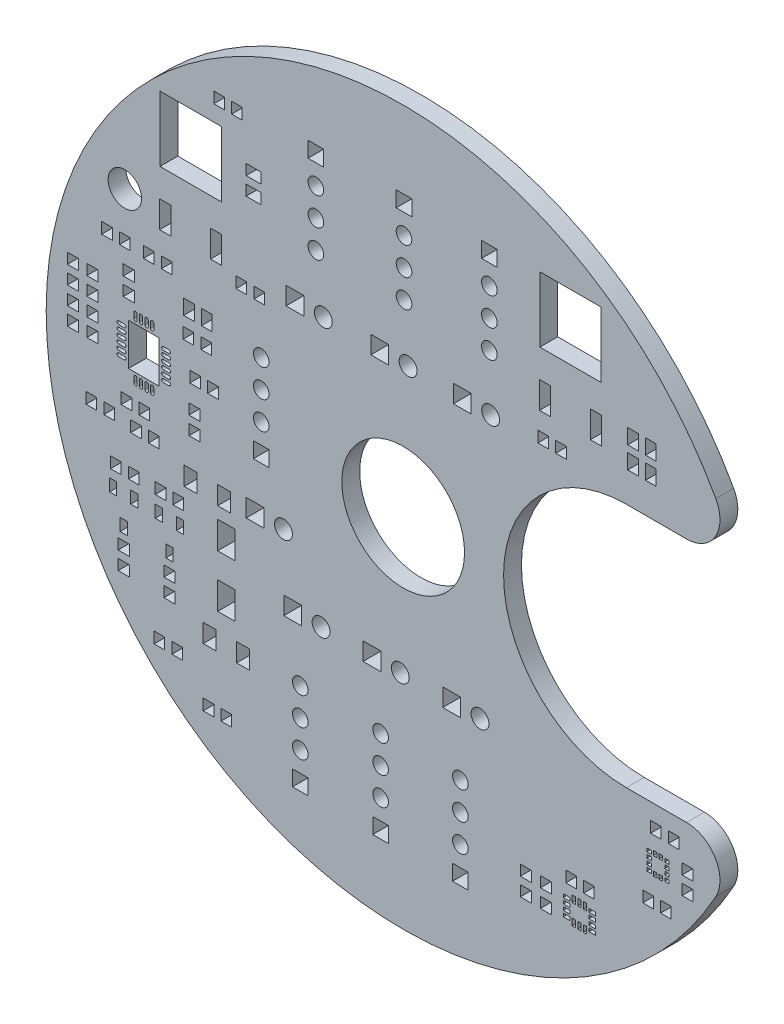
SolidWorks part; units mm, degrees
ref_plane "Plan de face" through (0, 0, 0) normal (0, 0, 1) x (1, 0, 0)
ref_plane "Plan de dessus" through (0, 0, 0) normal (0, 1, 0) x (1, 0, 0)
ref_plane "Plan de droite" through (0, 0, 0) normal (1, 0, 0) x (0, 0, -1)
sketch "Model" plane through (0, 0, 0) normal (0, 0, 1) x (1, 0, 0)
  line L0 (23.85, -16.25) -> (23.85, -16.55)
  line L1 (23.85, -16.55) -> (23.45, -16.55)
  line L2 (23.45, -16.55) -> (23.45, -16.25)
  line L3 (23.45, -16.25) -> (23.85, -16.25)
  line L4 (23.85, -15.75) -> (23.85, -16.05)
  line L5 (23.85, -16.05) -> (23.45, -16.05)
  line L6 (23.45, -16.05) -> (23.45, -15.75)
  line L7 (23.45, -15.75) -> (23.85, -15.75)
  line L8 (23.85, -15.25) -> (23.85, -15.55)
  line L9 (23.85, -15.55) -> (23.45, -15.55)
  line L10 (23.45, -15.55) -> (23.45, -15.25)
  line L11 (23.45, -15.25) -> (23.85, -15.25)
  line L12 (23.85, -14.75) -> (23.85, -15.05)
  line L13 (23.85, -15.05) -> (23.45, -15.05)
  line L14 (23.45, -15.05) -> (23.45, -14.75)
  line L15 (23.45, -14.75) -> (23.85, -14.75)
  line L16 (22.95, -14.65) -> (23.25, -14.65)
  line L17 (23.25, -14.65) -> (23.25, -15.05)
  line L18 (23.25, -15.05) -> (22.95, -15.05)
  line L19 (22.95, -15.05) -> (22.95, -14.65)
  line L20 (22.45, -14.65) -> (22.75, -14.65)
  line L21 (22.75, -14.65) -> (22.75, -15.05)
  line L22 (22.75, -15.05) -> (22.45, -15.05)
  line L23 (22.45, -15.05) -> (22.45, -14.65)
  line L24 (22.25, -14.75) -> (22.25, -15.05)
  line L25 (22.25, -15.05) -> (21.85, -15.05)
  line L26 (21.85, -15.05) -> (21.85, -14.75)
  line L27 (21.85, -14.75) -> (22.25, -14.75)
  line L28 (22.25, -15.25) -> (22.25, -15.55)
  line L29 (22.25, -15.55) -> (21.85, -15.55)
  line L30 (21.85, -15.55) -> (21.85, -15.25)
  line L31 (21.85, -15.25) -> (22.25, -15.25)
  line L32 (22.25, -15.75) -> (22.25, -16.05)
  line L33 (22.25, -16.05) -> (21.85, -16.05)
  line L34 (21.85, -16.05) -> (21.85, -15.75)
  line L35 (21.85, -15.75) -> (22.25, -15.75)
  line L36 (22.25, -16.25) -> (22.25, -16.55)
  line L37 (22.25, -16.55) -> (21.85, -16.55)
  line L38 (21.85, -16.55) -> (21.85, -16.25)
  line L39 (21.85, -16.25) -> (22.25, -16.25)
  line L40 (22.45, -16.25) -> (22.75, -16.25)
  line L41 (22.75, -16.25) -> (22.75, -16.65)
  line L42 (22.75, -16.65) -> (22.45, -16.65)
  line L43 (22.45, -16.65) -> (22.45, -16.25)
  line L44 (22.95, -16.25) -> (23.25, -16.25)
  line L45 (23.25, -16.25) -> (23.25, -16.65)
  line L46 (23.25, -16.65) -> (22.95, -16.65)
  line L47 (22.95, -16.65) -> (22.95, -16.25)
  line L48 (17.25, -23.55) -> (17.25, -23.85)
  line L49 (17.25, -23.85) -> (16.65, -23.85)
  line L50 (16.65, -23.85) -> (16.65, -23.55)
  line L51 (16.65, -23.55) -> (17.25, -23.55)
  line L52 (17.25, -23.05) -> (17.25, -23.35)
  line L53 (17.25, -23.35) -> (16.65, -23.35)
  line L54 (16.65, -23.35) -> (16.65, -23.05)
  line L55 (16.65, -23.05) -> (17.25, -23.05)
  line L56 (17.25, -22.55) -> (17.25, -22.85)
  line L57 (17.25, -22.85) -> (16.65, -22.85)
  line L58 (16.65, -22.85) -> (16.65, -22.55)
  line L59 (16.65, -22.55) -> (17.25, -22.55)
  line L60 (17.25, -22.05) -> (17.25, -22.35)
  line L61 (17.25, -22.35) -> (16.65, -22.35)
  line L62 (16.65, -22.35) -> (16.65, -22.05)
  line L63 (16.65, -22.05) -> (17.25, -22.05)
  line L64 (16.15, -21.75) -> (16.45, -21.75)
  line L65 (16.45, -21.75) -> (16.45, -22.35)
  line L66 (16.45, -22.35) -> (16.15, -22.35)
  line L67 (16.15, -22.35) -> (16.15, -21.75)
  line L68 (15.65, -21.75) -> (15.95, -21.75)
  line L69 (15.95, -21.75) -> (15.95, -22.35)
  line L70 (15.95, -22.35) -> (15.65, -22.35)
  line L71 (15.65, -22.35) -> (15.65, -21.75)
  line L72 (15.15, -21.75) -> (15.45, -21.75)
  line L73 (15.45, -21.75) -> (15.45, -22.35)
  line L74 (15.45, -22.35) -> (15.15, -22.35)
  line L75 (15.15, -22.35) -> (15.15, -21.75)
  line L76 (14.95, -22.05) -> (14.95, -22.35)
  line L77 (14.95, -22.35) -> (14.35, -22.35)
  line L78 (14.35, -22.35) -> (14.35, -22.05)
  line L79 (14.35, -22.05) -> (14.95, -22.05)
  line L80 (14.95, -22.55) -> (14.95, -22.85)
  line L81 (14.95, -22.85) -> (14.35, -22.85)
  line L82 (14.35, -22.85) -> (14.35, -22.55)
  line L83 (14.35, -22.55) -> (14.95, -22.55)
  line L84 (14.95, -23.05) -> (14.95, -23.35)
  line L85 (14.95, -23.35) -> (14.35, -23.35)
  line L86 (14.35, -23.35) -> (14.35, -23.05)
  line L87 (14.35, -23.05) -> (14.95, -23.05)
  line L88 (14.95, -23.55) -> (14.95, -23.85)
  line L89 (14.95, -23.85) -> (14.35, -23.85)
  line L90 (14.35, -23.85) -> (14.35, -23.55)
  line L91 (14.35, -23.55) -> (14.95, -23.55)
  line L92 (15.15, -23.55) -> (15.45, -23.55)
  line L93 (15.45, -23.55) -> (15.45, -24.15)
  line L94 (15.45, -24.15) -> (15.15, -24.15)
  line L95 (15.15, -24.15) -> (15.15, -23.55)
  line L96 (15.65, -23.55) -> (15.95, -23.55)
  line L97 (15.95, -23.55) -> (15.95, -24.15)
  line L98 (15.95, -24.15) -> (15.65, -24.15)
  line L99 (15.65, -24.15) -> (15.65, -23.55)
  line L100 (16.15, -23.55) -> (16.45, -23.55)
  line L101 (16.45, -23.55) -> (16.45, -24.15)
  line L102 (16.45, -24.15) -> (16.15, -24.15)
  line L103 (16.15, -24.15) -> (16.15, -23.55)
  line L104 (-18.075, 7.175) -> (-17.125, 7.175)
  line L105 (-17.125, 7.175) -> (-17.125, 5.825)
  line L106 (-17.125, 5.825) -> (-18.075, 5.825)
  line L107 (-18.075, 5.825) -> (-18.075, 7.175)
  line L108 (-19.675, 7.175) -> (-18.725, 7.175)
  line L109 (-18.725, 7.175) -> (-18.725, 5.825)
  line L110 (-18.725, 5.825) -> (-19.675, 5.825)
  line L111 (-19.675, 5.825) -> (-19.675, 7.175)
  line L112 (-21.5, 0) -> (-21, 0)
  line L113 (-21, -0.3) -> (-21.5, -0.3)
  line L114 (-21.5, 0.5) -> (-21, 0.5)
  line L115 (-21, 0.2) -> (-21.5, 0.2)
  line L116 (-21.5, 1) -> (-21, 1)
  line L117 (-21, 0.7) -> (-21.5, 0.7)
  line L118 (-21.5, 1.5) -> (-21, 1.5)
  line L119 (-21, 1.2) -> (-21.5, 1.2)
  line L120 (-21.5, 2) -> (-21, 2)
  line L121 (-21, 1.7) -> (-21.5, 1.7)
  line L122 (-21.5, 2.5) -> (-21, 2.5)
  line L123 (-21, 2.2) -> (-21.5, 2.2)
  line L124 (-22.65, 3.35) -> (-22.65, 3.85)
  line L125 (-22.35, 3.85) -> (-22.35, 3.35)
  line L126 (-23.15, 3.35) -> (-23.15, 3.85)
  line L127 (-22.85, 3.85) -> (-22.85, 3.35)
  line L128 (-23.65, 3.35) -> (-23.65, 3.85)
  line L129 (-23.35, 3.85) -> (-23.35, 3.35)
  line L130 (-24.15, 3.35) -> (-24.15, 3.85)
  line L131 (-23.85, 3.85) -> (-23.85, 3.35)
  line L132 (-25.5, 2.5) -> (-25, 2.5)
  line L133 (-25, 2.2) -> (-25.5, 2.2)
  line L134 (-25.5, 2) -> (-25, 2)
  line L135 (-25, 1.7) -> (-25.5, 1.7)
  line L136 (-25.5, 1.5) -> (-25, 1.5)
  line L137 (-25, 1.2) -> (-25.5, 1.2)
  line L138 (-25.5, 1) -> (-25, 1)
  line L139 (-25, 0.7) -> (-25.5, 0.7)
  line L140 (-25.5, 0.5) -> (-25, 0.5)
  line L141 (-25, 0.2) -> (-25.5, 0.2)
  line L142 (-25.5, 0) -> (-25, 0)
  line L143 (-25, -0.3) -> (-25.5, -0.3)
  line L144 (-24.15, -1.65) -> (-24.15, -1.15)
  line L145 (-23.85, -1.15) -> (-23.85, -1.65)
  line L146 (-23.65, -1.65) -> (-23.65, -1.15)
  line L147 (-23.35, -1.15) -> (-23.35, -1.65)
  line L148 (-23.15, -1.65) -> (-23.15, -1.15)
  line L149 (-22.85, -1.15) -> (-22.85, -1.65)
  line L150 (-22.65, -1.65) -> (-22.65, -1.15)
  line L151 (-22.35, -1.15) -> (-22.35, -1.65)
  line L152 (-21.875, 2.975) -> (-21.875, -0.775)
  line L153 (-21.875, -0.775) -> (-24.625, -0.775)
  line L154 (-24.625, -0.775) -> (-24.625, 2.975)
  line L155 (-24.625, 2.975) -> (-21.875, 2.975)
  line L156 (-24.425, -10.1) -> (-23.775, -10.1)
  line L157 (-23.775, -10.1) -> (-23.775, -11.2)
  line L158 (-23.775, -11.2) -> (-24.425, -11.2)
  line L159 (-24.425, -11.2) -> (-24.425, -10.1)
  line L160 (-26.325, -10.1) -> (-25.675, -10.1)
  line L161 (-25.675, -10.1) -> (-25.675, -11.2)
  line L162 (-25.675, -11.2) -> (-26.325, -11.2)
  line L163 (-26.325, -11.2) -> (-26.325, -10.1)
  line L164 (-25.375, -12.7) -> (-24.725, -12.7)
  line L165 (-24.725, -12.7) -> (-24.725, -13.8)
  line L166 (-24.725, -13.8) -> (-25.375, -13.8)
  line L167 (-25.375, -13.8) -> (-25.375, -12.7)
  line L168 (-20.325, -10.1) -> (-19.675, -10.1)
  line L169 (-19.675, -10.1) -> (-19.675, -11.2)
  line L170 (-19.675, -11.2) -> (-20.325, -11.2)
  line L171 (-20.325, -11.2) -> (-20.325, -10.1)
  line L172 (-22.225, -10.1) -> (-21.575, -10.1)
  line L173 (-21.575, -10.1) -> (-21.575, -11.2)
  line L174 (-21.575, -11.2) -> (-22.225, -11.2)
  line L175 (-22.225, -11.2) -> (-22.225, -10.1)
  line L176 (-21.275, -12.7) -> (-20.625, -12.7)
  line L177 (-20.625, -12.7) -> (-20.625, -13.8)
  line L178 (-20.625, -13.8) -> (-21.275, -13.8)
  line L179 (-21.275, -13.8) -> (-21.275, -12.7)
  line L180 (21.725, 15.075) -> (22.675, 15.075)
  line L181 (22.675, 15.075) -> (22.675, 13.725)
  line L182 (22.675, 13.725) -> (21.725, 13.725)
  line L183 (21.725, 13.725) -> (21.725, 15.075)
  line L184 (20.125, 15.075) -> (21.075, 15.075)
  line L185 (21.075, 15.075) -> (21.075, 13.725)
  line L186 (21.075, 13.725) -> (20.125, 13.725)
  line L187 (20.125, 13.725) -> (20.125, 15.075)
  line L188 (-14.075, 19.475) -> (-14.075, 20.425)
  line L189 (-14.075, 20.425) -> (-12.725, 20.425)
  line L190 (-12.725, 20.425) -> (-12.725, 19.475)
  line L191 (-12.725, 19.475) -> (-14.075, 19.475)
  line L192 (-14.075, 17.875) -> (-14.075, 18.825)
  line L193 (-14.075, 18.825) -> (-12.725, 18.825)
  line L194 (-12.725, 18.825) -> (-12.725, 17.875)
  line L195 (-12.725, 17.875) -> (-14.075, 17.875)
  line L196 (21.075, 15.675) -> (20.125, 15.675)
  line L197 (20.125, 15.675) -> (20.125, 17.025)
  line L198 (20.125, 17.025) -> (21.075, 17.025)
  line L199 (21.075, 17.025) -> (21.075, 15.675)
  line L200 (22.675, 15.675) -> (21.725, 15.675)
  line L201 (21.725, 15.675) -> (21.725, 17.025)
  line L202 (21.725, 17.025) -> (22.675, 17.025)
  line L203 (22.675, 17.025) -> (22.675, 15.675)
  line L204 (-20.83, 11.4) -> (-21.83, 11.4)
  line L205 (-21.83, 11.4) -> (-21.83, 13.8)
  line L206 (-21.83, 13.8) -> (-20.83, 13.8)
  line L207 (-20.83, 13.8) -> (-20.83, 11.4)
  line L208 (-16.27, 11.4) -> (-17.27, 11.4)
  line L209 (-17.27, 11.4) -> (-17.27, 13.8)
  line L210 (-17.27, 13.8) -> (-16.27, 13.8)
  line L211 (-16.27, 13.8) -> (-16.27, 11.4)
  line L212 (-16.3, 16.325) -> (-21.8, 16.325)
  line L213 (-21.8, 16.325) -> (-21.8, 22.175)
  line L214 (-21.8, 22.175) -> (-16.3, 22.175)
  line L215 (-16.3, 22.175) -> (-16.3, 16.325)
  line L216 (13.22, 14.4) -> (12.22, 14.4)
  line L217 (12.22, 14.4) -> (12.22, 16.8)
  line L218 (12.22, 16.8) -> (13.22, 16.8)
  line L219 (13.22, 16.8) -> (13.22, 14.4)
  line L220 (17.78, 14.4) -> (16.78, 14.4)
  line L221 (16.78, 14.4) -> (16.78, 16.8)
  line L222 (16.78, 16.8) -> (17.78, 16.8)
  line L223 (17.78, 16.8) -> (17.78, 14.4)
  line L224 (17.75, 19.325) -> (12.25, 19.325)
  line L225 (12.25, 19.325) -> (12.25, 25.175)
  line L226 (12.25, 25.175) -> (17.75, 25.175)
  line L227 (17.75, 25.175) -> (17.75, 19.325)
  line L228 (-16.025, 23.6) -> (-16.975, 23.6)
  line L229 (-16.975, 23.6) -> (-16.975, 24.6)
  line L230 (-16.975, 24.6) -> (-16.025, 24.6)
  line L231 (-16.025, 24.6) -> (-16.025, 23.6)
  line L232 (-14.425, 23.6) -> (-15.375, 23.6)
  line L233 (-15.375, 23.6) -> (-15.375, 24.6)
  line L234 (-15.375, 24.6) -> (-14.425, 24.6)
  line L235 (-14.425, 24.6) -> (-14.425, 23.6)
  line L236 (-20.725, -20) -> (-19.775, -20)
  line L237 (-19.775, -20) -> (-19.775, -21)
  line L238 (-19.775, -21) -> (-20.725, -21)
  line L239 (-20.725, -21) -> (-20.725, -20)
  line L240 (-22.325, -20) -> (-21.375, -20)
  line L241 (-21.375, -20) -> (-21.375, -21)
  line L242 (-21.375, -21) -> (-22.325, -21)
  line L243 (-22.325, -21) -> (-22.325, -20)
  line L244 (-16.975, -24) -> (-17.925, -24)
  line L245 (-17.925, -24) -> (-17.925, -23)
  line L246 (-17.925, -23) -> (-16.975, -23)
  line L247 (-16.975, -23) -> (-16.975, -24)
  line L248 (-15.375, -24) -> (-16.325, -24)
  line L249 (-16.325, -24) -> (-16.325, -23)
  line L250 (-16.325, -23) -> (-15.375, -23)
  line L251 (-15.375, -23) -> (-15.375, -24)
  line L252 (-14.025, 10.25) -> (-14.975, 10.25)
  line L253 (-14.975, 10.25) -> (-14.975, 11.25)
  line L254 (-14.975, 11.25) -> (-14.025, 11.25)
  line L255 (-14.025, 11.25) -> (-14.025, 10.25)
  line L256 (-12.425, 10.25) -> (-13.375, 10.25)
  line L257 (-13.375, 10.25) -> (-13.375, 11.25)
  line L258 (-13.375, 11.25) -> (-12.425, 11.25)
  line L259 (-12.425, 11.25) -> (-12.425, 10.25)
  line L260 (23.775, -12.45) -> (24.725, -12.45)
  line L261 (24.725, -12.45) -> (24.725, -13.45)
  line L262 (24.725, -13.45) -> (23.775, -13.45)
  line L263 (23.775, -13.45) -> (23.775, -12.45)
  line L264 (22.175, -12.45) -> (23.125, -12.45)
  line L265 (23.125, -12.45) -> (23.125, -13.45)
  line L266 (23.125, -13.45) -> (22.175, -13.45)
  line L267 (22.175, -13.45) -> (22.175, -12.45)
  line L268 (23.075, -18.2) -> (24.025, -18.2)
  line L269 (24.025, -18.2) -> (24.025, -19.2)
  line L270 (24.025, -19.2) -> (23.075, -19.2)
  line L271 (23.075, -19.2) -> (23.075, -18.2)
  line L272 (21.475, -18.2) -> (22.425, -18.2)
  line L273 (22.425, -18.2) -> (22.425, -19.2)
  line L274 (22.425, -19.2) -> (21.475, -19.2)
  line L275 (21.475, -19.2) -> (21.475, -18.2)
  line L276 (26, -15.925) -> (26, -16.875)
  line L277 (26, -16.875) -> (25, -16.875)
  line L278 (25, -16.875) -> (25, -15.925)
  line L279 (25, -15.925) -> (26, -15.925)
  line L280 (26, -14.325) -> (26, -15.275)
  line L281 (26, -15.275) -> (25, -15.275)
  line L282 (25, -15.275) -> (25, -14.325)
  line L283 (25, -14.325) -> (26, -14.325)
  line L284 (15.525, -21.1) -> (14.575, -21.1)
  line L285 (14.575, -21.1) -> (14.575, -20.1)
  line L286 (14.575, -20.1) -> (15.525, -20.1)
  line L287 (15.525, -20.1) -> (15.525, -21.1)
  line L288 (17.125, -21.1) -> (16.175, -21.1)
  line L289 (16.175, -21.1) -> (16.175, -20.1)
  line L290 (16.175, -20.1) -> (17.125, -20.1)
  line L291 (17.125, -20.1) -> (17.125, -21.1)
  line L292 (11.5, -23.275) -> (11.5, -24.225)
  line L293 (11.5, -24.225) -> (10.5, -24.225)
  line L294 (10.5, -24.225) -> (10.5, -23.275)
  line L295 (10.5, -23.275) -> (11.5, -23.275)
  line L296 (11.5, -21.675) -> (11.5, -22.625)
  line L297 (11.5, -22.625) -> (10.5, -22.625)
  line L298 (10.5, -22.625) -> (10.5, -21.675)
  line L299 (10.5, -21.675) -> (11.5, -21.675)
  line L300 (13.3, -23.275) -> (13.3, -24.225)
  line L301 (13.3, -24.225) -> (12.3, -24.225)
  line L302 (12.3, -24.225) -> (12.3, -23.275)
  line L303 (12.3, -23.275) -> (13.3, -23.275)
  line L304 (13.3, -21.675) -> (13.3, -22.625)
  line L305 (13.3, -22.625) -> (12.3, -22.625)
  line L306 (12.3, -22.625) -> (12.3, -21.675)
  line L307 (12.3, -21.675) -> (13.3, -21.675)
  line L308 (-18.775, 3.95) -> (-19.725, 3.95)
  line L309 (-19.725, 3.95) -> (-19.725, 4.95)
  line L310 (-19.725, 4.95) -> (-18.775, 4.95)
  line L311 (-18.775, 4.95) -> (-18.775, 3.95)
  line L312 (-17.175, 3.95) -> (-18.125, 3.95)
  line L313 (-18.125, 3.95) -> (-18.125, 4.95)
  line L314 (-18.125, 4.95) -> (-17.175, 4.95)
  line L315 (-17.175, 4.95) -> (-17.175, 3.95)
  line L316 (-23.675, -2.9) -> (-22.725, -2.9)
  line L317 (-22.725, -2.9) -> (-22.725, -3.9)
  line L318 (-22.725, -3.9) -> (-23.675, -3.9)
  line L319 (-23.675, -3.9) -> (-23.675, -2.9)
  line L320 (-25.275, -2.9) -> (-24.325, -2.9)
  line L321 (-24.325, -2.9) -> (-24.325, -3.9)
  line L322 (-24.325, -3.9) -> (-25.275, -3.9)
  line L323 (-25.275, -3.9) -> (-25.275, -2.9)
  line L324 (-26.825, -4.45) -> (-25.875, -4.45)
  line L325 (-25.875, -4.45) -> (-25.875, -5.45)
  line L326 (-25.875, -5.45) -> (-26.825, -5.45)
  line L327 (-26.825, -5.45) -> (-26.825, -4.45)
  line L328 (-28.425, -4.45) -> (-27.475, -4.45)
  line L329 (-27.475, -4.45) -> (-27.475, -5.45)
  line L330 (-27.475, -5.45) -> (-28.425, -5.45)
  line L331 (-28.425, -5.45) -> (-28.425, -4.45)
  line L332 (-25.1, 6.175) -> (-25.1, 7.125)
  line L333 (-25.1, 7.125) -> (-24.1, 7.125)
  line L334 (-24.1, 7.125) -> (-24.1, 6.175)
  line L335 (-24.1, 6.175) -> (-25.1, 6.175)
  line L336 (-25.1, 4.575) -> (-25.1, 5.525)
  line L337 (-25.1, 5.525) -> (-24.1, 5.525)
  line L338 (-24.1, 5.525) -> (-24.1, 4.575)
  line L339 (-24.1, 4.575) -> (-25.1, 4.575)
  line L340 (-17.525, 1.85) -> (-16.575, 1.85)
  line L341 (-16.575, 1.85) -> (-16.575, 0.85)
  line L342 (-16.575, 0.85) -> (-17.525, 0.85)
  line L343 (-17.525, 0.85) -> (-17.525, 1.85)
  line L344 (-19.125, 1.85) -> (-18.175, 1.85)
  line L345 (-18.175, 1.85) -> (-18.175, 0.85)
  line L346 (-18.175, 0.85) -> (-19.125, 0.85)
  line L347 (-19.125, 0.85) -> (-19.125, 1.85)
  line L348 (-18.2, -2.325) -> (-18.2, -3.275)
  line L349 (-18.2, -3.275) -> (-19.2, -3.275)
  line L350 (-19.2, -3.275) -> (-19.2, -2.325)
  line L351 (-19.2, -2.325) -> (-18.2, -2.325)
  line L352 (-18.2, -0.725) -> (-18.2, -1.675)
  line L353 (-18.2, -1.675) -> (-19.2, -1.675)
  line L354 (-19.2, -1.675) -> (-19.2, -0.725)
  line L355 (-19.2, -0.725) -> (-18.2, -0.725)
  line L356 (-22.825, -4.65) -> (-21.875, -4.65)
  line L357 (-21.875, -4.65) -> (-21.875, -5.65)
  line L358 (-21.875, -5.65) -> (-22.825, -5.65)
  line L359 (-22.825, -5.65) -> (-22.825, -4.65)
  line L360 (-24.425, -4.65) -> (-23.475, -4.65)
  line L361 (-23.475, -4.65) -> (-23.475, -5.65)
  line L362 (-23.475, -5.65) -> (-24.425, -5.65)
  line L363 (-24.425, -5.65) -> (-24.425, -4.65)
  line L364 (-29.1, 0.725) -> (-29.1, -0.225)
  line L365 (-29.1, -0.225) -> (-30.1, -0.225)
  line L366 (-30.1, -0.225) -> (-30.1, 0.725)
  line L367 (-30.1, 0.725) -> (-29.1, 0.725)
  line L368 (-29.1, 2.325) -> (-29.1, 1.375)
  line L369 (-29.1, 1.375) -> (-30.1, 1.375)
  line L370 (-30.1, 1.375) -> (-30.1, 2.325)
  line L371 (-30.1, 2.325) -> (-29.1, 2.325)
  line L372 (-27.35, 0.725) -> (-27.35, -0.225)
  line L373 (-27.35, -0.225) -> (-28.35, -0.225)
  line L374 (-28.35, -0.225) -> (-28.35, 0.725)
  line L375 (-28.35, 0.725) -> (-27.35, 0.725)
  line L376 (-27.35, 2.325) -> (-27.35, 1.375)
  line L377 (-27.35, 1.375) -> (-28.35, 1.375)
  line L378 (-28.35, 1.375) -> (-28.35, 2.325)
  line L379 (-28.35, 2.325) -> (-27.35, 2.325)
  line L380 (-29.1, 3.925) -> (-29.1, 2.975)
  line L381 (-29.1, 2.975) -> (-30.1, 2.975)
  line L382 (-30.1, 2.975) -> (-30.1, 3.925)
  line L383 (-30.1, 3.925) -> (-29.1, 3.925)
  line L384 (-29.1, 5.525) -> (-29.1, 4.575)
  line L385 (-29.1, 4.575) -> (-30.1, 4.575)
  line L386 (-30.1, 4.575) -> (-30.1, 5.525)
  line L387 (-30.1, 5.525) -> (-29.1, 5.525)
  line L388 (-27.35, 3.925) -> (-27.35, 2.975)
  line L389 (-27.35, 2.975) -> (-28.35, 2.975)
  line L390 (-28.35, 2.975) -> (-28.35, 3.925)
  line L391 (-28.35, 3.925) -> (-27.35, 3.925)
  line L392 (-27.35, 5.525) -> (-27.35, 4.575)
  line L393 (-27.35, 4.575) -> (-28.35, 4.575)
  line L394 (-28.35, 4.575) -> (-28.35, 5.525)
  line L395 (-28.35, 5.525) -> (-27.35, 5.525)
  line L396 (-22.325, 8.45) -> (-23.275, 8.45)
  line L397 (-23.275, 8.45) -> (-23.275, 9.45)
  line L398 (-23.275, 9.45) -> (-22.325, 9.45)
  line L399 (-22.325, 9.45) -> (-22.325, 8.45)
  line L400 (-20.725, 8.45) -> (-21.675, 8.45)
  line L401 (-21.675, 8.45) -> (-21.675, 9.45)
  line L402 (-21.675, 9.45) -> (-20.725, 9.45)
  line L403 (-20.725, 9.45) -> (-20.725, 8.45)
  line L404 (-26.075, 8.45) -> (-27.025, 8.45)
  line L405 (-27.025, 8.45) -> (-27.025, 9.45)
  line L406 (-27.025, 9.45) -> (-26.075, 9.45)
  line L407 (-26.075, 9.45) -> (-26.075, 8.45)
  line L408 (-24.475, 8.45) -> (-25.425, 8.45)
  line L409 (-25.425, 8.45) -> (-25.425, 9.45)
  line L410 (-25.425, 9.45) -> (-24.475, 9.45)
  line L411 (-24.475, 9.45) -> (-24.475, 8.45)
  line L412 (-24.625, -8.35) -> (-23.675, -8.35)
  line L413 (-23.675, -8.35) -> (-23.675, -9.35)
  line L414 (-23.675, -9.35) -> (-24.625, -9.35)
  line L415 (-24.625, -9.35) -> (-24.625, -8.35)
  line L416 (-26.225, -8.35) -> (-25.275, -8.35)
  line L417 (-25.275, -8.35) -> (-25.275, -9.35)
  line L418 (-25.275, -9.35) -> (-26.225, -9.35)
  line L419 (-26.225, -9.35) -> (-26.225, -8.35)
  line L420 (-24.55, -15.975) -> (-24.55, -16.925)
  line L421 (-24.55, -16.925) -> (-25.55, -16.925)
  line L422 (-25.55, -16.925) -> (-25.55, -15.975)
  line L423 (-25.55, -15.975) -> (-24.55, -15.975)
  line L424 (-24.55, -14.375) -> (-24.55, -15.325)
  line L425 (-24.55, -15.325) -> (-25.55, -15.325)
  line L426 (-25.55, -15.325) -> (-25.55, -14.375)
  line L427 (-25.55, -14.375) -> (-24.55, -14.375)
  line L428 (-20.625, -8.35) -> (-19.675, -8.35)
  line L429 (-19.675, -8.35) -> (-19.675, -9.35)
  line L430 (-19.675, -9.35) -> (-20.625, -9.35)
  line L431 (-20.625, -9.35) -> (-20.625, -8.35)
  line L432 (-22.225, -8.35) -> (-21.275, -8.35)
  line L433 (-21.275, -8.35) -> (-21.275, -9.35)
  line L434 (-21.275, -9.35) -> (-22.225, -9.35)
  line L435 (-22.225, -9.35) -> (-22.225, -8.35)
  line L436 (-20.45, -16.025) -> (-20.45, -16.975)
  line L437 (-20.45, -16.975) -> (-21.45, -16.975)
  line L438 (-21.45, -16.975) -> (-21.45, -16.025)
  line L439 (-21.45, -16.025) -> (-20.45, -16.025)
  line L440 (-20.45, -14.425) -> (-20.45, -15.375)
  line L441 (-20.45, -15.375) -> (-21.45, -15.375)
  line L442 (-21.45, -15.375) -> (-21.45, -14.425)
  line L443 (-21.45, -14.425) -> (-20.45, -14.425)
  line L444 (13.675, 12.8) -> (14.625, 12.8)
  line L445 (14.625, 12.8) -> (14.625, 11.8)
  line L446 (14.625, 11.8) -> (13.675, 11.8)
  line L447 (13.675, 11.8) -> (13.675, 12.8)
  line L448 (12.075, 12.8) -> (13.025, 12.8)
  line L449 (13.025, 12.8) -> (13.025, 11.8)
  line L450 (13.025, 11.8) -> (12.075, 11.8)
  line L451 (12.075, 11.8) -> (12.075, 12.8)
  line L452 (-16.775, -18.775) -> (-17.925, -18.775)
  line L453 (-17.925, -18.775) -> (-17.925, -17.125)
  line L454 (-17.925, -17.125) -> (-16.775, -17.125)
  line L455 (-16.775, -17.125) -> (-16.775, -18.775)
  line L456 (-13.775, -18.775) -> (-14.925, -18.775)
  line L457 (-14.925, -18.775) -> (-14.925, -17.125)
  line L458 (-14.925, -17.125) -> (-13.775, -17.125)
  line L459 (-13.775, -17.125) -> (-13.775, -18.775)
  line L460 (-18.475, -7.425) -> (-19.625, -7.425)
  line L461 (-19.625, -7.425) -> (-19.625, -5.775)
  line L462 (-19.625, -5.775) -> (-18.475, -5.775)
  line L463 (-18.475, -5.775) -> (-18.475, -7.425)
  line L464 (-15.475, -7.425) -> (-16.625, -7.425)
  line L465 (-16.625, -7.425) -> (-16.625, -5.775)
  line L466 (-16.625, -5.775) -> (-15.475, -5.775)
  line L467 (-15.475, -5.775) -> (-15.475, -7.425)
  line L468 (-16.625, -8.475) -> (-15.075, -8.475)
  line L469 (-15.075, -8.475) -> (-15.075, -10.925)
  line L470 (-15.075, -10.925) -> (-16.625, -10.925)
  line L471 (-16.625, -10.925) -> (-16.625, -8.475)
  line L472 (-16.625, -13.175) -> (-15.075, -13.175)
  line L473 (-15.075, -13.175) -> (-15.075, -15.625)
  line L474 (-15.075, -15.625) -> (-16.625, -15.625)
  line L475 (-16.625, -15.625) -> (-16.625, -13.175)
  line L476 (-12.025, -2.175) -> (-13.425, -2.175)
  line L477 (-13.425, -2.175) -> (-13.425, -0.775)
  line L478 (-13.425, -0.775) -> (-12.025, -0.775)
  line L479 (-12.025, -0.775) -> (-12.025, -2.175)
  line L480 (-8.525, -25.9) -> (-9.925, -25.9)
  line L481 (-9.925, -25.9) -> (-9.925, -24.5)
  line L482 (-9.925, -24.5) -> (-8.525, -24.5)
  line L483 (-8.525, -24.5) -> (-8.525, -25.9)
  line L484 (5.825, -26.05) -> (4.425, -26.05)
  line L485 (4.425, -26.05) -> (4.425, -24.65)
  line L486 (4.425, -24.65) -> (5.825, -24.65)
  line L487 (5.825, -24.65) -> (5.825, -26.05)
  line L488 (-1.325, -26.0001) -> (-2.725, -26.0001)
  line L489 (-2.725, -26.0001) -> (-2.725, -24.6001)
  line L490 (-2.725, -24.6001) -> (-1.325, -24.6001)
  line L491 (-1.325, -24.6001) -> (-1.325, -26.0001)
  line L492 (-8.525, 24.9999) -> (-7.125, 24.9999)
  line L493 (-7.125, 24.9999) -> (-7.125, 23.5999)
  line L494 (-7.125, 23.5999) -> (-8.525, 23.5999)
  line L495 (-8.525, 23.5999) -> (-8.525, 24.9999)
  line L496 (7.025, 25) -> (8.425, 25)
  line L497 (8.425, 25) -> (8.425, 23.6)
  line L498 (8.425, 23.6) -> (7.025, 23.6)
  line L499 (7.025, 23.6) -> (7.025, 25)
  line L500 (-0.625, 25.1) -> (0.775, 25.1)
  line L501 (0.775, 25.1) -> (0.775, 23.7)
  line L502 (0.775, 23.7) -> (-0.625, 23.7)
  line L503 (-0.625, 23.7) -> (-0.625, 25.1)
  line L504 (3.55, -13) -> (3.55, -11.4)
  line L505 (3.55, -11.4) -> (5.15, -11.4)
  line L506 (5.15, -11.4) -> (5.15, -13)
  line L507 (5.15, -13) -> (3.55, -13)
  line L508 (-3.6, -13) -> (-3.6, -11.4)
  line L509 (-3.6, -11.4) -> (-2, -11.4)
  line L510 (-2, -11.4) -> (-2, -13)
  line L511 (-2, -13) -> (-3.6, -13)
  line L512 (-10.7, -13) -> (-10.7, -11.4)
  line L513 (-10.7, -11.4) -> (-9.1, -11.4)
  line L514 (-9.1, -11.4) -> (-9.1, -13)
  line L515 (-9.1, -13) -> (-10.7, -13)
  line L516 (-10.5, 11.15) -> (-10.5, 12.75)
  line L517 (-10.5, 12.75) -> (-8.9, 12.75)
  line L518 (-8.9, 12.75) -> (-8.9, 11.15)
  line L519 (-8.9, 11.15) -> (-10.5, 11.15)
  line L520 (-2.9, 11.15) -> (-2.9, 12.75)
  line L521 (-2.9, 12.75) -> (-1.3, 12.75)
  line L522 (-1.3, 12.75) -> (-1.3, 11.15)
  line L523 (-1.3, 11.15) -> (-2.9, 11.15)
  line L524 (4.5, 11.05) -> (4.5, 12.65)
  line L525 (4.5, 12.65) -> (6.1, 12.65)
  line L526 (6.1, 12.65) -> (6.1, 11.05)
  line L527 (6.1, 11.05) -> (4.5, 11.05)
  line L528 (-14.07, -7.1) -> (-14.07, -5.5)
  line L529 (-14.07, -5.5) -> (-12.47, -5.5)
  line L530 (-12.47, -5.5) -> (-12.47, -7.1)
  line L531 (-12.47, -7.1) -> (-14.07, -7.1)
  line L532 (20, 11) -> (25.3969, 11)
  line L533 (25.3969, -11) -> (20, -11)
  circle A0 centre (-24.95, 13) radius 1.5
  circle A1 centre (-12.725, 1.025) radius 0.7
  circle A2 centre (-12.725, 3.525) radius 0.7
  circle A3 centre (-12.725, 6.025) radius 0.7
  circle A4 centre (-9.225, -22.7) radius 0.7
  circle A5 centre (-9.225, -20.2) radius 0.7
  circle A6 centre (-9.225, -17.7) radius 0.7
  circle A7 centre (5.125, -22.85) radius 0.7
  circle A8 centre (5.125, -20.35) radius 0.7
  circle A9 centre (5.125, -17.85) radius 0.7
  circle A10 centre (-2.025, -22.8001) radius 0.7
  circle A11 centre (-2.025, -20.3001) radius 0.7
  circle A12 centre (-2.025, -17.8001) radius 0.7
  circle A13 centre (-7.825, 21.7999) radius 0.7
  circle A14 centre (-7.825, 19.2999) radius 0.7
  circle A15 centre (-7.825, 16.7999) radius 0.7
  circle A16 centre (7.725, 21.8) radius 0.7
  circle A17 centre (7.725, 19.3) radius 0.7
  circle A18 centre (7.725, 16.8) radius 0.7
  circle A19 centre (0.075, 21.9) radius 0.7
  circle A20 centre (0.075, 19.4) radius 0.7
  circle A21 centre (0.075, 16.9) radius 0.7
  circle A22 centre (6.89, -12.2) radius 0.8
  circle A23 centre (-0.26, -12.2) radius 0.8
  circle A24 centre (-7.36, -12.2) radius 0.8
  circle A25 centre (-7.16, 11.95) radius 0.8
  circle A26 centre (0.44, 11.95) radius 0.8
  circle A27 centre (7.84, 11.85) radius 0.8
  circle A28 centre (-10.73, -6.3) radius 0.8
  arc A29 (-21, -0.3) -> (-21, 0) centre (-21, -0.15) ccw
  arc A30 (-21.5, 0) -> (-21.5, -0.3) centre (-21.5, -0.15) ccw
  arc A31 (-21, 0.2) -> (-21, 0.5) centre (-21, 0.35) ccw
  arc A32 (-21.5, 0.5) -> (-21.5, 0.2) centre (-21.5, 0.35) ccw
  arc A33 (-21, 0.7) -> (-21, 1) centre (-21, 0.85) ccw
  arc A34 (-21.5, 1) -> (-21.5, 0.7) centre (-21.5, 0.85) ccw
  arc A35 (-21, 1.2) -> (-21, 1.5) centre (-21, 1.35) ccw
  arc A36 (-21.5, 1.5) -> (-21.5, 1.2) centre (-21.5, 1.35) ccw
  arc A37 (-21, 1.7) -> (-21, 2) centre (-21, 1.85) ccw
  arc A38 (-21.5, 2) -> (-21.5, 1.7) centre (-21.5, 1.85) ccw
  arc A39 (-21, 2.2) -> (-21, 2.5) centre (-21, 2.35) ccw
  arc A40 (-21.5, 2.5) -> (-21.5, 2.2) centre (-21.5, 2.35) ccw
  arc A41 (-22.35, 3.85) -> (-22.65, 3.85) centre (-22.5, 3.85) ccw
  arc A42 (-22.65, 3.35) -> (-22.35, 3.35) centre (-22.5, 3.35) ccw
  arc A43 (-22.85, 3.85) -> (-23.15, 3.85) centre (-23, 3.85) ccw
  arc A44 (-23.15, 3.35) -> (-22.85, 3.35) centre (-23, 3.35) ccw
  arc A45 (-23.35, 3.85) -> (-23.65, 3.85) centre (-23.5, 3.85) ccw
  arc A46 (-23.65, 3.35) -> (-23.35, 3.35) centre (-23.5, 3.35) ccw
  arc A47 (-23.85, 3.85) -> (-24.15, 3.85) centre (-24, 3.85) ccw
  arc A48 (-24.15, 3.35) -> (-23.85, 3.35) centre (-24, 3.35) ccw
  arc A49 (-25, 2.2) -> (-25, 2.5) centre (-25, 2.35) ccw
  arc A50 (-25.5, 2.5) -> (-25.5, 2.2) centre (-25.5, 2.35) ccw
  arc A51 (-25, 1.7) -> (-25, 2) centre (-25, 1.85) ccw
  arc A52 (-25.5, 2) -> (-25.5, 1.7) centre (-25.5, 1.85) ccw
  arc A53 (-25, 1.2) -> (-25, 1.5) centre (-25, 1.35) ccw
  arc A54 (-25.5, 1.5) -> (-25.5, 1.2) centre (-25.5, 1.35) ccw
  arc A55 (-25, 0.7) -> (-25, 1) centre (-25, 0.85) ccw
  arc A56 (-25.5, 1) -> (-25.5, 0.7) centre (-25.5, 0.85) ccw
  arc A57 (-25, 0.2) -> (-25, 0.5) centre (-25, 0.35) ccw
  arc A58 (-25.5, 0.5) -> (-25.5, 0.2) centre (-25.5, 0.35) ccw
  arc A59 (-25, -0.3) -> (-25, 0) centre (-25, -0.15) ccw
  arc A60 (-25.5, 0) -> (-25.5, -0.3) centre (-25.5, -0.15) ccw
  arc A61 (-23.85, -1.15) -> (-24.15, -1.15) centre (-24, -1.15) ccw
  arc A62 (-24.15, -1.65) -> (-23.85, -1.65) centre (-24, -1.65) ccw
  arc A63 (-23.35, -1.15) -> (-23.65, -1.15) centre (-23.5, -1.15) ccw
  arc A64 (-23.65, -1.65) -> (-23.35, -1.65) centre (-23.5, -1.65) ccw
  arc A65 (-22.85, -1.15) -> (-23.15, -1.15) centre (-23, -1.15) ccw
  arc A66 (-23.15, -1.65) -> (-22.85, -1.65) centre (-23, -1.65) ccw
  arc A67 (-22.35, -1.15) -> (-22.65, -1.15) centre (-22.5, -1.15) ccw
  arc A68 (-22.65, -1.65) -> (-22.35, -1.65) centre (-22.5, -1.65) ccw
  arc A69 (25.3969, 11) -> (28.0241, 15.4483) centre (25.3969, 14) ccw
  arc A70 (20, 11) -> (20, -11) centre (20, 0) ccw
  arc A71 (28.0241, -15.4483) -> (25.3969, -11) centre (25.3969, -14) ccw
  arc A72 (28.0241, 15.4483) -> (28.0241, -15.4483) centre (0, 0) ccw
  circle A73 centre (0, 0) radius 5.5
extrude "Boss.-Extru.1" add sketch "Model" along normal blind 1.6
